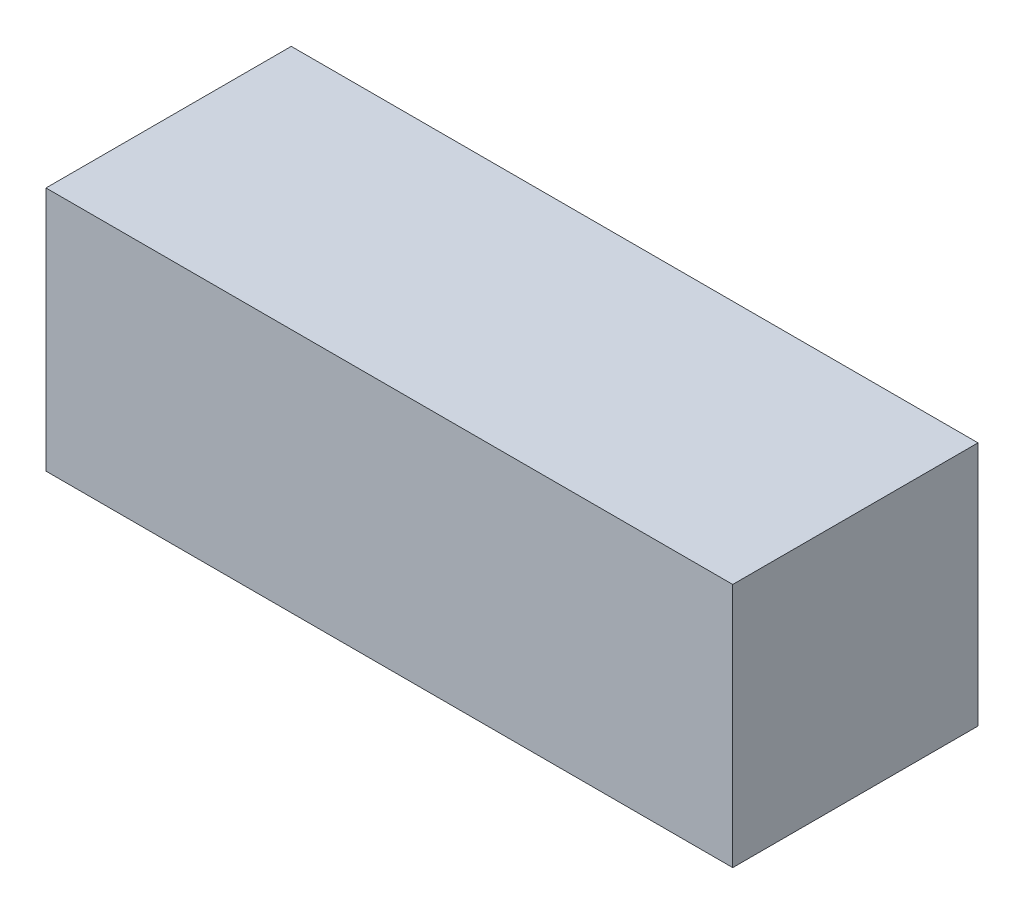
SolidWorks part; units mm, degrees
ref_plane "Спереди" through (0, 0, 0) normal (0, 0, 1) x (1, 0, 0)
ref_plane "Сверху" through (0, 0, 0) normal (0, 1, 0) x (1, 0, 0)
ref_plane "Справа" through (0, 0, 0) normal (1, 0, 0) x (0, 0, -1)
sketch "Эскиз2" plane through (0, 0, 0) normal (0, 0, 1) x (1, 0, 0)
  line L1 (0, 0) -> (140, 0)
  line L2 (0, 0) -> (0, 50)
  line L3 (0, 50) -> (140, 50)
  line L4 (140, 0) -> (140, 50)
  dimension "D1" = 140
  dimension "D2" = 50
extrude "Бобышка-Вытянуть1" add sketch "Эскиз2" along normal blind 50
